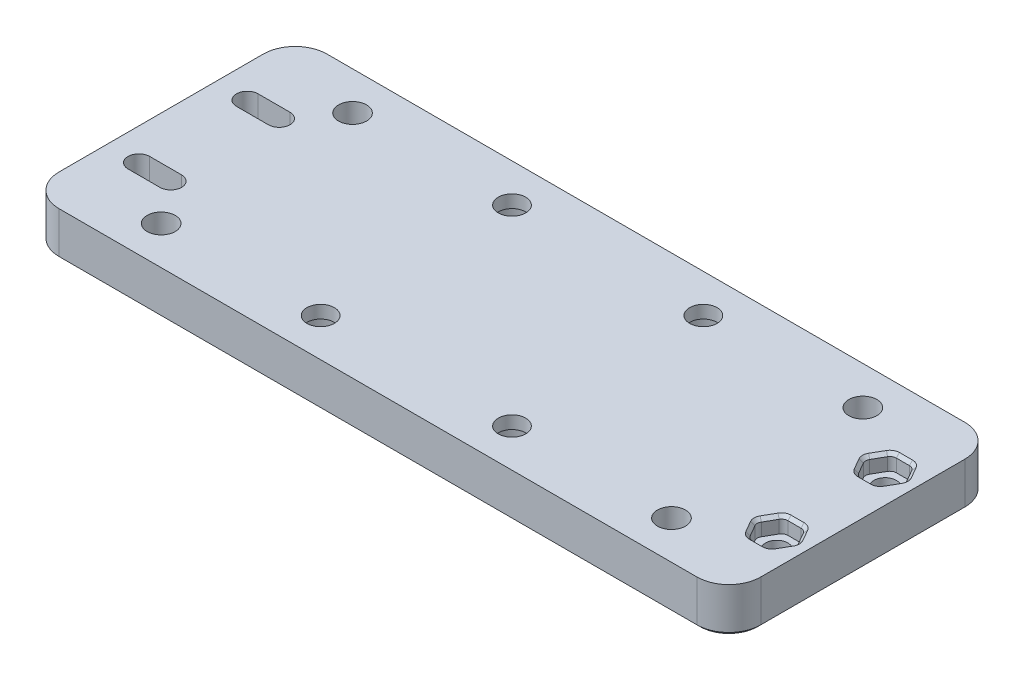
SolidWorks part; units mm, degrees
ref_plane "Front Plane" through (0, 0, 0) normal (0, 0, 1) x (1, 0, 0)
ref_plane "Top Plane" through (0, 0, 0) normal (0, 1, 0) x (1, 0, 0)
ref_plane "Right Plane" through (0, 0, 0) normal (1, 0, 0) x (0, 0, -1)
sketch "Sketch1" plane through (0, 0, 0) normal (0, 1, 0) x (1, 0, 0)
  line L1 (-55, -21) -> (55, -21)
  line L2 (-55, -21) -> (-55, 21)
  line L3 (-55, 21) -> (55, 21)
  line L4 (55, -21) -> (55, 21)
  line L5 (-55, -21) -> (55, 21) construction
  line L6 (-55, 21) -> (55, -21) construction
  line L7 (-50, -8.5) -> (50, -8.5) construction
  line L8 (-50, -8.5) -> (-50, 8.5) construction
  line L9 (-50, 8.5) -> (50, 8.5) construction
  line L10 (50, -8.5) -> (50, 8.5) construction
  line L11 (-50, -8.5) -> (50, 8.5) construction
  line L12 (-50, 8.5) -> (50, -8.5) construction
  line L13 (-15, -15) -> (15, -15) construction
  line L14 (-15, -15) -> (-15, 15) construction
  line L15 (-15, 15) -> (15, 15) construction
  line L16 (15, -15) -> (15, 15) construction
  line L17 (-15, -15) -> (15, 15) construction
  line L18 (-15, 15) -> (15, -15) construction
  point P0 (0, 0)
  point P6 (0, 0)
  point P11 (0, 0)
  point P17 (15, 15)
  point P18 (-15, 15)
  point P19 (15, -15)
  point P20 (-15, -15)
  point P21 (-50, -8.5)
  point P22 (-50, 8.5)
  point P23 (50, 8.5)
  point P24 (50, -8.5)
  dimension "D1" = 42
  dimension "D2" = 5
  dimension "D3" = 100
  dimension "D4" = 17
  dimension "D5" = 30
  dimension "D6" = 30
extrude "Boss-Extrude1" add sketch "Sketch1" along normal blind 7
sketch "Sketch15" plane through (0, 0, 0) normal (0, -1, 0) x (1, 0, 0)
  line L1 (40, 15) -> (-40, 15) construction
  line L2 (40, 15) -> (40, -15) construction
  line L3 (40, -15) -> (-40, -15) construction
  line L4 (-40, 15) -> (-40, -15) construction
  line L5 (40, 15) -> (-40, -15) construction
  line L6 (40, -15) -> (-40, 15) construction
  point P0 (0, 0)
  dimension "D1" = 80
  dimension "D2" = 30
hole_wizard "Ø4.4 (4.4) Diameter Hole1" positions "Sketch16" profile "Sketch17" hole size "Ø4.4" standard "ISO" end condition through all
sketch "Sketch16" plane through (0, 0, 0) normal (0, -1, 0) x (-1, 0, 0)
  point P0 (-40, 15)
  point P3 (-40, -15)
  point P6 (40, -15)
  point P9 (40, 15)
sketch "Sketch17" plane through (40, 0, -15) normal (1, 0, 0) x (0, 0, -1)
  line L0 (0, 0) -> (0, 7)
  line L1 (0, 7) -> (2.2, 7)
  line L2 (2.2, 7) -> (2.2, 0)
  line L5 (2.2, 0) -> (0, 0)
  line L11 (0, -6.35) -> (0, 107.95) construction
  dimension "Thru Hole Dia." = 4.4
  dimension "Thru Hole Depth" = 7
hole_wizard "CBORE for M4 Hex Socket Head Cap Screw1" positions "Sketch11" profile "Sketch12" counterbore size "M4" standard "ISO" end condition through all
sketch "Sketch11" plane through (0, 0, 0) normal (0, -1, 0) x (-1, 0, 0)
  point P0 (-15, 15)
  point P3 (15, 15)
  point P6 (-15, -15)
  point P9 (15, -15)
sketch "Sketch12" plane through (15, 0, -15) normal (1, 0, 0) x (0, 0, -1)
  line L0 (0, 0) -> (0, 7)
  line L1 (0, 7) -> (2.15, 7)
  line L3 (2.15, 7) -> (2.15, 5)
  line L4 (2.15, 5) -> (4, 5)
  line L5 (4, 5) -> (4, 0)
  line L7 (4, 0) -> (0, 0)
  line L11 (0, -6.35) -> (0, 107.95) construction
  dimension "Thru Hole Dia." = 4.3
  dimension "Thru Hole Depth" = 7
  dimension "C'Bore Dia." = 8
  dimension "C'Bore Depth" = 5
sketch "Sketch18" plane through (0, 0, 0) normal (0, -1, 0) x (1, 0, 0)
  line L0 (-50, 8.5) -> (-45, 8.5) construction
  line L1 (-50, 10.2) -> (-45, 10.2)
  line L2 (-50, 6.8) -> (-45, 6.8)
  line L3 (-50, -8.5) -> (-45, -8.5) construction
  line L4 (-50, -6.8) -> (-45, -6.8)
  line L5 (-50, -10.2) -> (-45, -10.2)
  arc A0 (-50, 10.2) -> (-50, 6.8) centre (-50, 8.5) ccw
  arc A1 (-45, 6.8) -> (-45, 10.2) centre (-45, 8.5) ccw
  arc A2 (-50, -6.8) -> (-50, -10.2) centre (-50, -8.5) ccw
  arc A3 (-45, -10.2) -> (-45, -6.8) centre (-45, -8.5) ccw
  circle A4 centre (50, 8.5) radius 1.75
  circle A5 centre (50, -8.5) radius 1.75
  point P3 (-47.5, 8.5)
  point P8 (-47.5, -8.5)
  dimension "D3" = 3.5
  dimension "D1" = 3.4
  dimension "D2" = 5
extrude "Cut-Extrude1" cut sketch "Sketch18" against normal blind 10
fillet "Fillet1" radius 5 4 edges at (-55, 3.5, -21) (55, 3.5, -21) (55, 3.5, 21) (-55, 3.5, 21)
chamfer "Chamfer1" distance 0.5 angle 45 26 edges at (-53.5355, 0, 19.5355) (0, 0, 21) (53.5355, 0, 19.5355) (55, 0, 0) (53.5355, 0, -19.5355) (0, 0, -21) (-53.5355, 0, -19.5355) (-55, 0, 0) (-15, 0, 11) (15, 0, 11) (-15, 0, -19) (15, 0, -19) (-40, 0, -17.2) (-40, 0, 12.8) (40, 0, 12.8) (40, 0, -17.2) (-47.5, 0, 6.8) (-43.3, 0, 8.5) (-47.5, 0, 10.2) (-51.7, 0, 8.5) (50, 0, -10.25) (50, 0, 6.75) (-47.5, 0, -10.2) (-43.3, 0, -8.5) (-47.5, 0, -6.8) (-51.7, 0, -8.5)
sketch "Sketch22" plane through (0, 7, 0) normal (0, 1, 0) x (1, 0, 0)
  line L1 (46.7957, -8.5) -> (48.3979, -11.275)
  line L2 (48.3979, -11.275) -> (51.6021, -11.275)
  line L3 (51.6021, -11.275) -> (53.2043, -8.5)
  line L4 (53.2043, -8.5) -> (51.6021, -5.725)
  line L5 (51.6021, -5.725) -> (48.3979, -5.725)
  line L6 (48.3979, -5.725) -> (46.7957, -8.5)
  line L7 (46.7957, 8.5) -> (48.3979, 5.725)
  line L8 (48.3979, 5.725) -> (51.6021, 5.725)
  line L9 (51.6021, 5.725) -> (53.2043, 8.5)
  line L10 (53.2043, 8.5) -> (51.6021, 11.275)
  line L11 (51.6021, 11.275) -> (48.3979, 11.275)
  line L12 (48.3979, 11.275) -> (46.7957, 8.5)
  circle A0 centre (50, -8.5) radius 2.775 construction
  circle A1 centre (50, 8.5) radius 2.775 construction
  dimension "D1" = 5.55
extrude "Cut-Extrude2" cut sketch "Sketch22" against normal blind 2.5
fillet "Fillet2" radius 1 12 edges at (51.6021, 5.75, 11.275) (53.2043, 5.75, 8.5) (51.6021, 5.75, 5.725) (48.3979, 5.75, 5.725) (46.7957, 5.75, 8.5) (48.3979, 5.75, 11.275) (48.3979, 5.75, -5.725) (46.7957, 5.75, -8.5) (48.3979, 5.75, -11.275) (51.6021, 5.75, -11.275) (53.2043, 5.75, -8.5) (51.6021, 5.75, -5.725)
chamfer "Chamfer2" distance 0.5 angle 45 24 edges at (50, 7, 11.275) (51.5248, 7, 11.141) (48.4752, 7, 11.141) (52.4032, 7, 9.8875) (47.5968, 7, 9.8875) (53.0496, 7, 8.5) (46.9504, 7, 8.5) (52.4032, 7, 7.1125) (47.5968, 7, 7.1125) (51.5248, 7, 5.859) (48.4752, 7, 5.859) (50, 7, 5.725) (50, 7, -11.275) (48.4752, 7, -11.141) (51.5248, 7, -11.141) (47.5968, 7, -9.8875) (52.4032, 7, -9.8875) (46.9504, 7, -8.5) (53.0496, 7, -8.5) (47.5968, 7, -7.1125) (52.4032, 7, -7.1125) (48.4752, 7, -5.859) (51.5248, 7, -5.859) (50, 7, -5.725)
